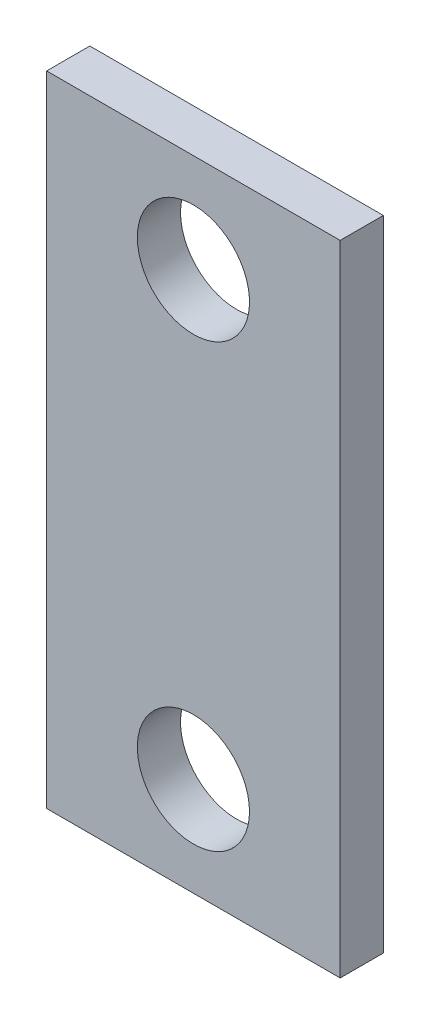
SolidWorks part; units mm, degrees
material "3003 Alloy"
ref_plane "X-Y Datum" through (0, 0, 0) normal (0, 0, 1) x (1, 0, 0)
ref_plane "X-Z Datum" through (0, 0, 0) normal (0, 1, 0) x (1, 0, 0)
ref_plane "Y-Z Datum" through (0, 0, 0) normal (1, 0, 0) x (0, 0, -1)
sketch "Sketch1" plane through (0, 0, 0) normal (0, 0, 1) x (1, 0, 0)
  line L0 (10.795, -5.0855) -> (10.795, -7.7372) construction
  line L1 (0, 0) -> (21.59, 0)
  line L2 (0, 0) -> (0, 46.99)
  line L3 (0, 46.99) -> (21.59, 46.99)
  line L4 (21.59, 0) -> (21.59, 46.99)
  line L5 (0, 23.495) -> (19.6604, 23.495) construction
  circle A0 centre (10.795, 7.2602) radius 4.125
  circle A1 centre (10.795, 39.7298) radius 4.125
  dimension "D1" = 46.99
extrude "Boss-Extrude1" add sketch "Sketch1" along normal blind 3.175 contours L0 A0 | A0 L0 | L3 L4 L1 L2 | A1
